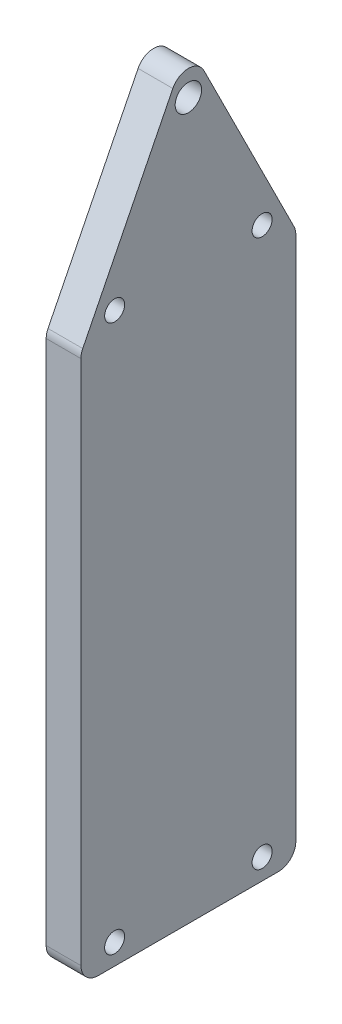
SolidWorks part; units mm, degrees
material "6061 Alloy"
ref_plane "Front Plane" through (0, 0, 0) normal (0, 0, 1) x (1, 0, 0)
ref_plane "Top Plane" through (0, 0, 0) normal (0, 1, 0) x (1, 0, 0)
ref_plane "Right Plane" through (0, 0, 0) normal (1, 0, 0) x (0, 0, -1)
sketch "Sketch1" plane through (0, 0, 0) normal (1, 0, 0) x (0, 0, -1)
  line L0 (-13.4747, 0) -> (13.4747, 0) construction
  line L1 (0, 0) -> (0, 26.9494) construction
  line L2 (-13.4747, 0) -> (0, 26.9494) construction
  line L3 (0, 26.9494) -> (13.4747, 0) construction
  line L4 (13.4747, 0) -> (-13.4747, 0) construction
  line L5 (19.6394, -3.81) -> (-19.6394, -3.81)
  line L6 (-19.6394, -3.81) -> (0, 35.4688)
  line L7 (0, 35.4688) -> (19.6394, -3.81)
  line L8 (-13.4747, 0) -> (13.4747, 0) construction
  line L9 (-13.4747, 0) -> (-13.4747, -100) construction
  line L10 (13.4747, 0) -> (13.4747, -100) construction
  line L11 (-13.4747, -100) -> (13.4747, -100) construction
  line L12 (-19.6394, -3.81) -> (19.6394, -3.81)
  line L13 (-19.6394, -3.81) -> (-19.6394, -103.81)
  line L14 (19.6394, -3.81) -> (19.6394, -103.81)
  line L15 (-19.6394, -103.81) -> (19.6394, -103.81)
  circle A0 centre (-13.4747, 0) radius 1.8288
  circle A1 centre (0, 26.9494) radius 2.413
  circle A2 centre (13.4747, 0) radius 1.8288
  circle A3 centre (-13.4747, -100) radius 1.8288
  circle A4 centre (13.4747, -100) radius 1.8288
  point P4 (0, 0)
  dimension "D3" = 3.6576
  dimension "D4" = 4.826
  dimension "D1" = 26.9494
  dimension "D5" = 100
  dimension "D6" = 3.81
  dimension "D2" = 3.81
extrude "Boss-Extrude1" add sketch "Sketch1" along normal blind 6.35 contours L13 L15 L14 L5 A4 A3 | L7 L6 L5 A2 A1 A0
fillet "Fillet1" radius 3.175 5 edges at (3.175, 35.4688, 0) (3.175, -103.81, 19.6394) (3.175, -103.81, -19.6394) (3.175, -3.81, 19.6394) (3.175, -3.81, -19.6394)
